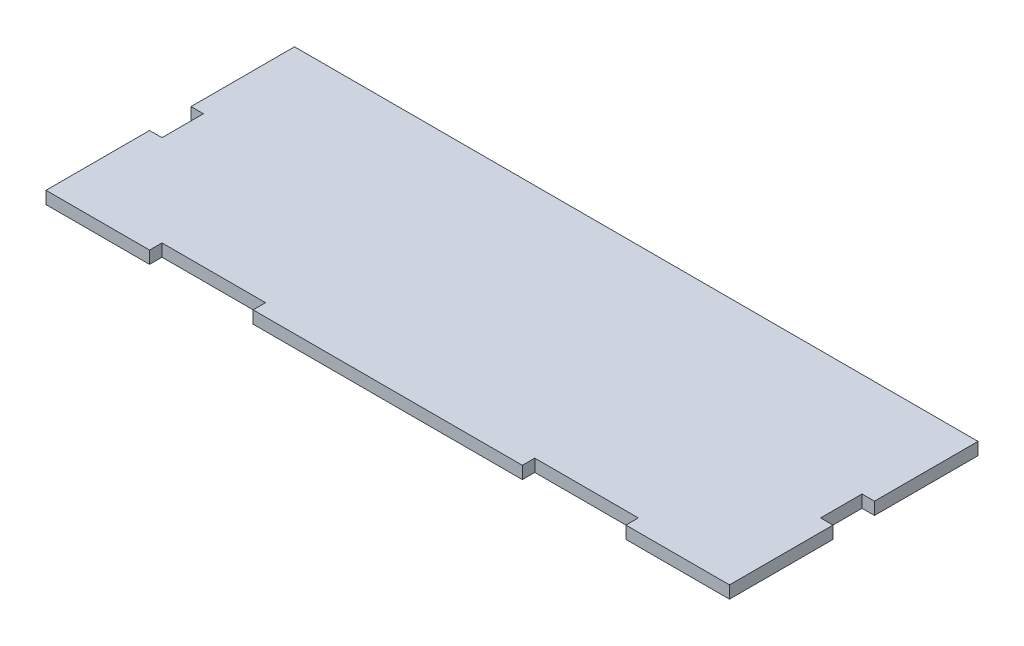
SolidWorks part; units mm, degrees
ref_plane "Front Plane" through (0, 0, 0) normal (0, 0, 1) x (1, 0, 0)
ref_plane "Top Plane" through (0, 0, 0) normal (0, 1, 0) x (1, 0, 0)
ref_plane "Right Plane" through (0, 0, 0) normal (1, 0, 0) x (0, 0, -1)
sketch "Sketch1" plane through (0, 0, 0) normal (0, 1, 0) x (1, 0, 0)
  line L1 (82.5, -30) -> (57.5, -30)
  line L2 (82.5, -30) -> (82.5, -5)
  line L3 (82.5, 30) -> (-82.5, 30)
  line L4 (-82.5, -30) -> (-82.5, -5)
  line L5 (82.5, -30) -> (-82.5, 30) construction
  line L6 (82.5, 30) -> (-82.5, -30) construction
  line L7 (-82.5, 5) -> (-82.5, 30)
  line L15 (32.5, -30) -> (-32.5, -30)
  line L16 (-57.5, -30) -> (-57.5, -27)
  line L17 (-57.5, -27) -> (-32.5, -27)
  line L18 (-32.5, -30) -> (-32.5, -27)
  line L19 (82.5, 5) -> (82.5, 30)
  line L20 (32.5, -30) -> (32.5, -27)
  line L21 (32.5, -27) -> (57.5, -27)
  line L22 (57.5, -30) -> (57.5, -27)
  line L23 (-82.5, 5) -> (-79.5, 5)
  line L24 (-57.5, -30) -> (-82.5, -30)
  line L25 (-82.5, -5) -> (-79.5, -5)
  line L26 (-79.5, 5) -> (-79.5, -5)
  line L27 (82.5, 5) -> (79.5, 5)
  line L29 (82.5, -5) -> (79.5, -5)
  line L30 (79.5, 5) -> (79.5, -5)
  point P0 (0, 0)
  dimension "D1" = 25
  dimension "D2" = 165
  dimension "D3" = 25
  dimension "D4" = 60
  dimension "D5" = 65
  dimension "D6" = 3
  dimension "D7" = 10
  dimension "D8" = 3
  dimension "D9" = 25
  dimension "D10" = 25
extrude "Boss-Extrude2" add sketch "Sketch1" along normal blind 3
